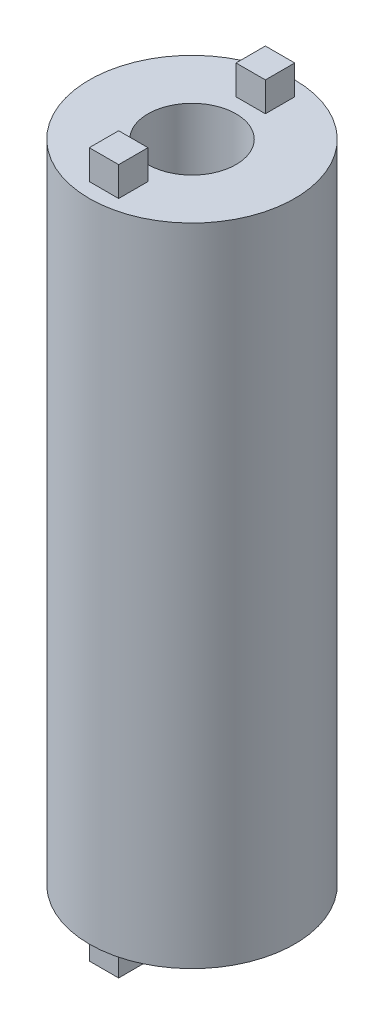
SolidWorks part; units mm, degrees
ref_plane "Front Plane" through (0, 0, 0) normal (0, 0, 1) x (1, 0, 0)
ref_plane "Top Plane" through (0, 0, 0) normal (0, 1, 0) x (1, 0, 0)
ref_plane "Right Plane" through (0, 0, 0) normal (1, 0, 0) x (0, 0, -1)
sketch "Sketch2" plane through (0, 0, 0) normal (0, 1, 0) x (1, 0, 0)
  circle A0 centre (0, 0) radius 3.5
  circle A1 centre (0, 0) radius 1.5
  dimension "D1" = 7
  dimension "D2" = 3
extrude "Boss-Extrude1" add sketch "Sketch2" along normal blind 22
sketch "Sketch3" plane through (0, 22, 0) normal (0, 1, 0) x (1, 0, 0)
  line L0 (0, 2.5) -> (0, -2.5) construction
  line L2 (-0.5, 3) -> (0.5, 3)
  line L3 (-0.5, 3) -> (-0.5, 2)
  line L4 (-0.5, 2) -> (0.5, 2)
  line L5 (0.5, 3) -> (0.5, 2)
  line L6 (-0.5, -2) -> (0.5, -2)
  line L7 (-0.5, -2) -> (-0.5, -3)
  line L8 (-0.5, -3) -> (0.5, -3)
  line L9 (0.5, -2) -> (0.5, -3)
  circle A0 centre (0, 0) radius 2.5 construction
  point P13 (0, 2)
  point P14 (0, -2)
  point P15 (-0.5, -2.5)
  point P16 (-0.5, 2.5)
  dimension "D1" = 5
  dimension "D2" = 1
extrude "Boss-Extrude2" add sketch "Sketch3" along normal blind 1
ref_plane "Plane1" through (0, 11, 0) normal (0, 1, 0) x (1, 0, 0)
mirror "Mirror1" about plane through (0, 11, 0) normal (0, 1, 0) of "Boss-Extrude2"
